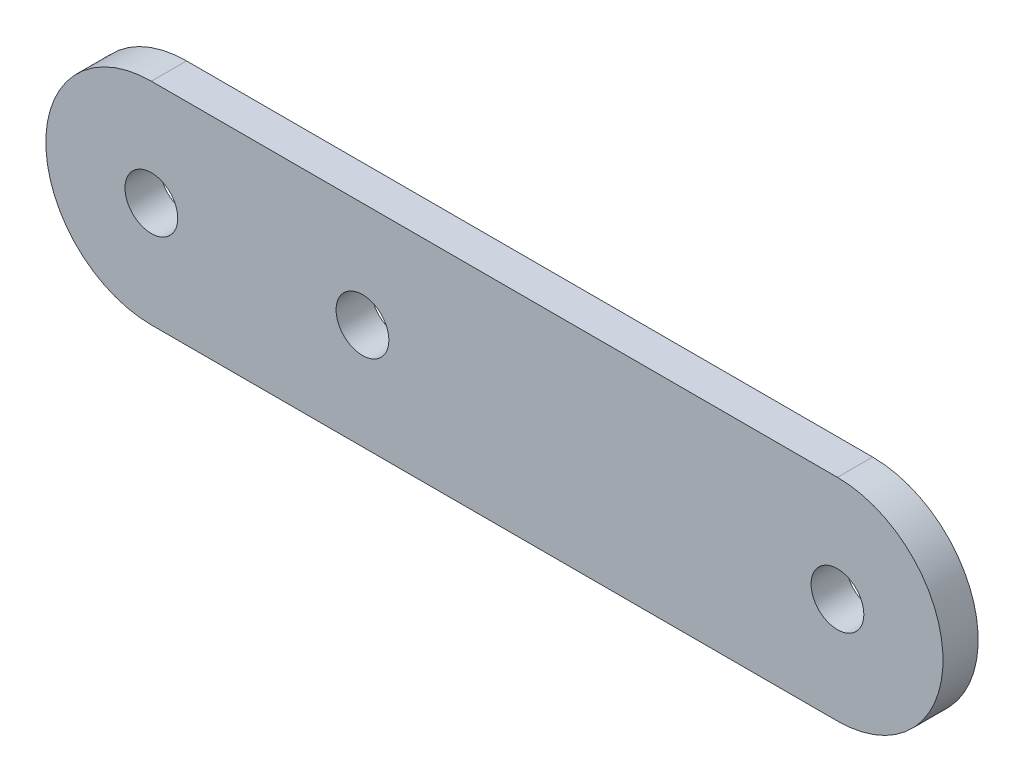
SolidWorks part; units mm, degrees
material "3.3535 (EN-AW 5754)"
ref_plane "Front" through (0, 0, 0) normal (0, 0, 1) x (1, 0, 0)
ref_plane "Top" through (0, 0, 0) normal (0, 1, 0) x (1, 0, 0)
ref_plane "Right" through (0, 0, 0) normal (1, 0, 0) x (0, 0, -1)
sketch "Esquisse1" plane through (0, 0, 0) normal (0, 0, 1) x (1, 0, 0)
  line L0 (0, 6) -> (39, 6)
  line L1 (39, -6) -> (0, -6)
  circle A0 centre (0, 0) radius 1.5
  circle A1 centre (39, 0) radius 1.5
  arc A2 (39, 6) -> (39, -6) centre (39, 0) cw
  arc A3 (0, -6) -> (0, 6) centre (0, 0) cw
  circle A4 centre (12, 0) radius 1.5
  point P13 (0, 0)
  dimension "D1" = 3
  dimension "D2" = 3
  dimension "D3" = 39
  dimension "D4" = 6
  dimension "D5" = 6
  dimension "D6" = 12
extrude "Boss.-Extru.1" add sketch "Esquisse1" along normal blind 2
